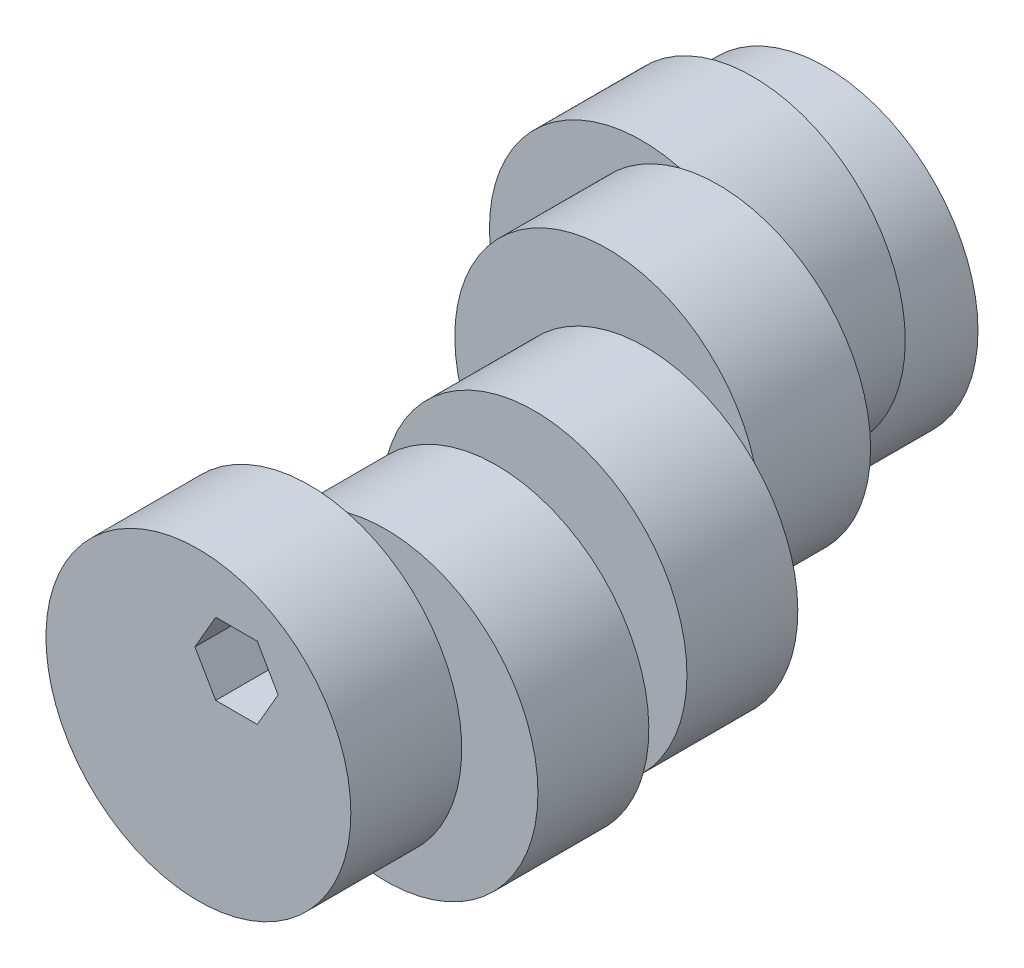
SolidWorks part; units mm, degrees
ref_plane "Front Plane" through (0, 0, 0) normal (0, 0, 1) x (1, 0, 0)
ref_plane "Top Plane" through (0, 0, 0) normal (0, 1, 0) x (1, 0, 0)
ref_plane "Right Plane" through (0, 0, 0) normal (1, 0, 0) x (0, 0, -1)
sketch "Sketch1" plane through (0, 0, 0) normal (0, 0, 1) x (1, 0, 0)
  circle A0 centre (0, 0) radius 11
extrude "Boss-Extrude1" add sketch "Sketch1" along normal blind 8
sketch "Sketch2" plane through (0, 0, 8) normal (0, 0, 1) x (1, 0, 0)
  line L0 (0, 0) -> (5.5, 0)
sketch "Sketch3" plane through (0, 0, 8) normal (0, 0, 1) x (1, 0, 0)
  line L0 (5.5, 0) -> (2.75, 4.7631)
  circle A0 centre (2.75, 4.7631) radius 11
extrude "Boss-Extrude2" add sketch "Sketch3" along normal blind 8 contours A0
sketch "Sketch4" plane through (0, 0, 16) normal (0, 0, 1) x (1, 0, 0)
  line L0 (5.5, 0) -> (8.25, 4.7631)
  circle A0 centre (8.25, 4.7631) radius 11
extrude "Boss-Extrude4" add sketch "Sketch4" along normal blind 8 contours A0
sketch "Sketch5" plane through (0, 0, 24) normal (0, 0, 1) x (1, 0, 0)
  line L0 (5.5, 0) -> (11, 0)
  circle A0 centre (11, 0) radius 11
extrude "Boss-Extrude5" add sketch "Sketch5" along normal blind 8 contours A0
sketch "Sketch6" plane through (0, 0, 32) normal (0, 0, 1) x (1, 0, 0)
  line L0 (5.5, 0) -> (8.25, -4.7631)
  circle A0 centre (8.25, -4.7631) radius 11
extrude "Boss-Extrude6" add sketch "Sketch6" along normal blind 8 contours A0
sketch "Sketch7" plane through (0, 0, 40) normal (0, 0, 1) x (1, 0, 0)
  line L0 (5.5, 0) -> (2.75, -4.7631)
sketch "Sketch8" plane through (0, 0, 40) normal (0, 0, 1) x (1, 0, 0)
  circle A0 centre (2.75, -4.7631) radius 11
  point P3 (0, 0)
  point P4 (3.8056, 2.9594)
extrude "Boss-Extrude7" add sketch "Sketch8" along normal blind 8
sketch "Sketch9" plane through (0, 0, 48) normal (0, 0, 1) x (1, 0, 0)
  line L1 (8.5, 0) -> (7, 2.5981)
  line L2 (7, 2.5981) -> (4, 2.5981)
  line L3 (4, 2.5981) -> (2.5, 0)
  line L4 (2.5, 0) -> (4, -2.5981)
  line L5 (4, -2.5981) -> (7, -2.5981)
  line L6 (7, -2.5981) -> (8.5, 0)
  circle A0 centre (5.5, 0) radius 3 construction
  point P1 (-17.0015, 3.2201)
  point P10 (7.0383, 5.5667)
extrude "Cut-Extrude1" cut sketch "Sketch9" against normal blind 48
